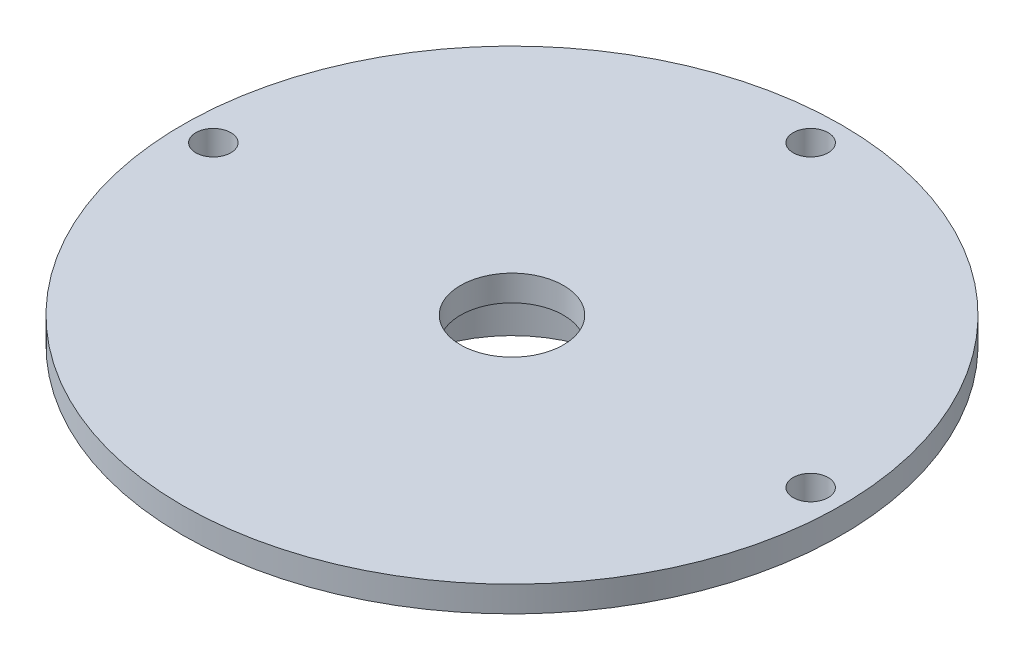
SolidWorks part; units mm, degrees
ref_plane "Alzado" through (0, 0, 0) normal (0, 0, 1) x (1, 0, 0)
ref_plane "Planta" through (0, 0, 0) normal (0, 1, 0) x (1, 0, 0)
ref_plane "Vista lateral" through (0, 0, 0) normal (1, 0, 0) x (0, 0, -1)
sketch "Croquis1" plane through (0, 0, 0) normal (0, 1, 0) x (1, 0, 0)
  line L0 (0, 0) -> (29, 0) construction
  line L1 (0, 0) -> (0, 29) construction
  line L2 (-29, 0) -> (0, 0) construction
  circle A0 centre (0, 0) radius 32
  circle A1 centre (29, 0) radius 1.7
  circle A3 centre (-29, 0) radius 1.7
  circle A4 centre (0, 29) radius 1.7
  circle A5 centre (0, -29) radius 1.7 [skipped]
  point P13 (0, 0)
  dimension "D1" = 64
  dimension "D3" = 3.4
  dimension "D2" = 29
  dimension "D5" = 29
  dimension "D6" = 29
  dimension "D4" = 4
extrude "Saliente-Extruir1" add sketch "Croquis1" along normal blind 2.5
sketch "Croquis2" plane through (0, 0, 0) normal (0, -1, 0) x (1, 0, 0)
  circle A0 centre (0, 0) radius 11
  circle A1 centre (0, 0) radius 16
  dimension "D1" = 22
  dimension "D2" = 32
extrude "Saliente-Extruir2" add sketch "Croquis2" along normal blind 7
sketch "Croquis3" plane through (0, 0, 0) normal (0, -1, 0) x (1, 0, 0)
  circle A0 centre (0, 0) radius 5
  dimension "D1" = 10
extrude "Cortar-Extruir1" cut sketch "Croquis3" against normal blind 7
